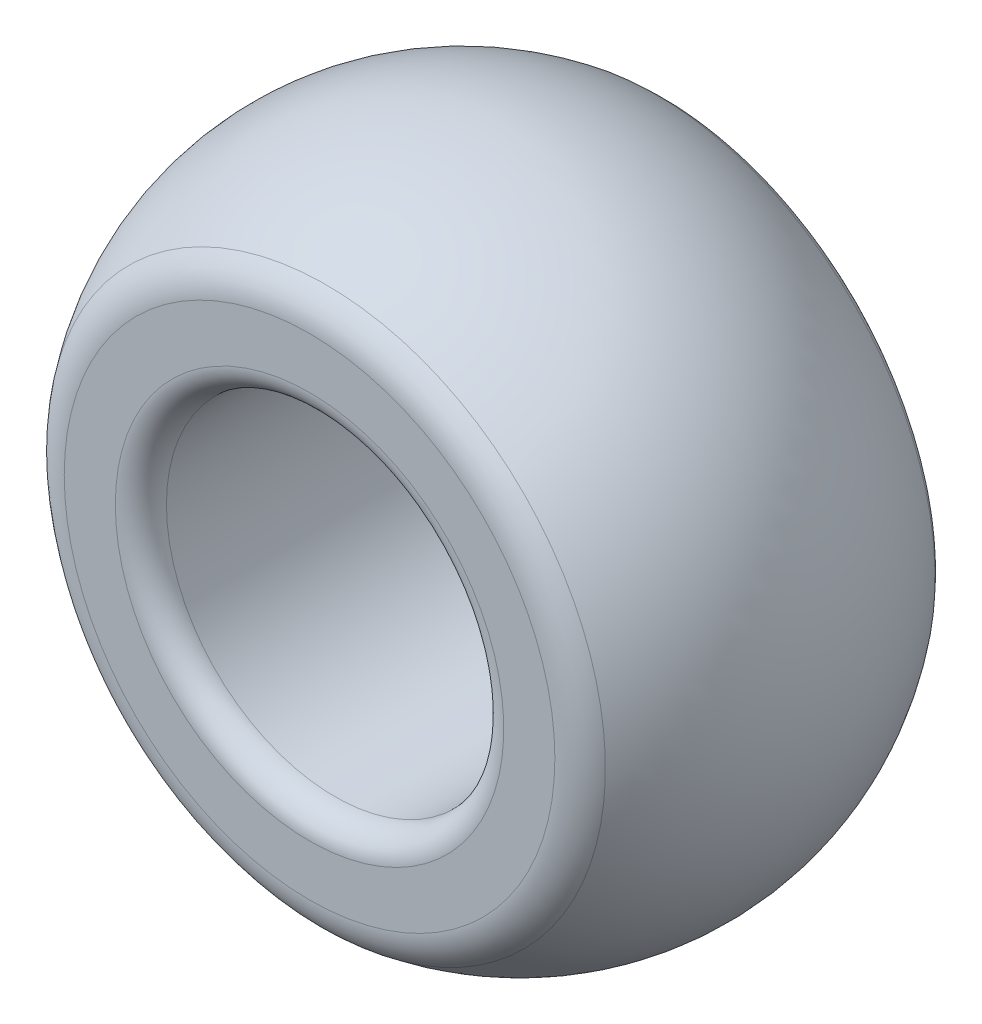
SolidWorks part; units mm, degrees
material "Brass"
ref_plane "Front Plane" through (0, 0, 0) normal (0, 0, 1) x (1, 0, 0)
ref_plane "Top Plane" through (0, 0, 0) normal (0, 1, 0) x (1, 0, 0)
ref_plane "Right Plane" through (0, 0, 0) normal (1, 0, 0) x (0, 0, -1)
sketch "Sketch1" plane through (0, 0, 0) normal (0, 1, 0) x (1, 0, 0)
  line L1 (-18.1968, 1.8341) -> (-18.1968, -0.0209)
  line L3 (-18.3488, 1.9861) -> (-18.6526, 1.9861)
  line L4 (-18.3488, -0.1729) -> (-18.6526, -0.1729)
  arc A0 (-18.8539, 1.887) -> (-18.8539, -0.0738) centre (-17.5794, 0.9066) ccw
  arc A1 (-18.3488, -0.1729) -> (-18.1968, -0.0209) centre (-18.3488, -0.0209) ccw
  arc A2 (-18.3488, 1.9861) -> (-18.1968, 1.8341) centre (-18.3488, 1.8341) cw
  arc A3 (-18.8539, 1.887) -> (-18.6526, 1.9861) centre (-18.6526, 1.7321) cw
  arc A4 (-18.8539, -0.0738) -> (-18.6526, -0.1729) centre (-18.6526, 0.0811) ccw
  point P3 (-17.1935, 1.4901)
  point P4 (-17.1935, 0.4929)
  point P9 (-12.4124, 0)
  point P12 (-12.4124, 2.159)
  dimension "D4" = 0.254
  dimension "D5" = 0.254
  dimension "D1" = 1.0033
  dimension "D2" = 2.159
  dimension "D3" = 1.0033
  dimension "D7" = 0.3859
ref_axis "Axis1" through (-17.1935, 0, -1.4901) along (0, 0, 1)
revolve "Revolve2" add sketch "Sketch1" angle 360 about axis through (-17.1935, 0, -1.4901) along (0, 0, 1)
